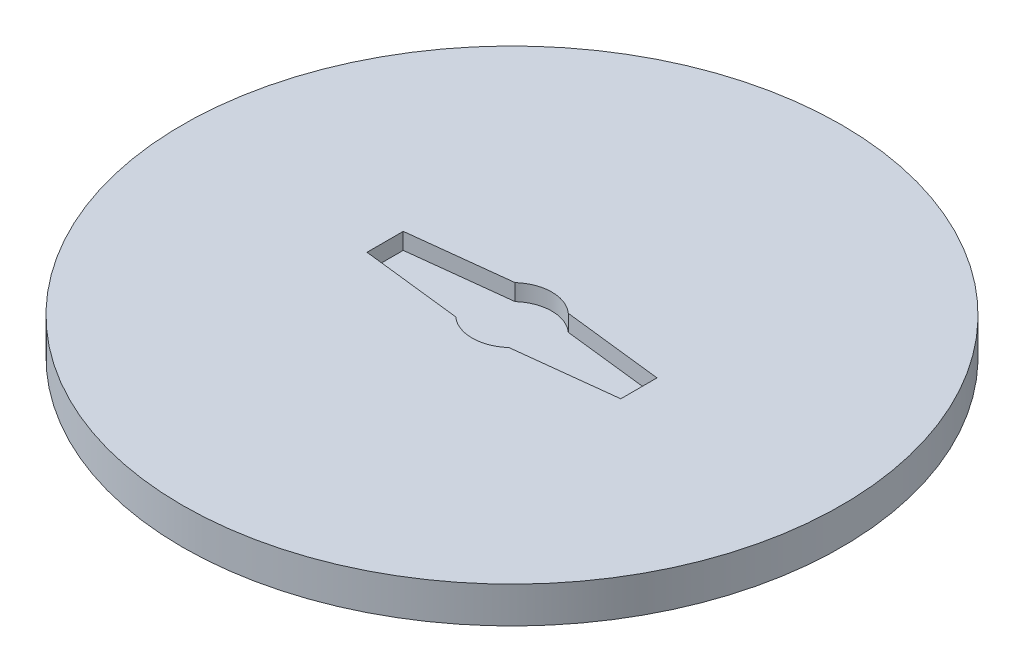
SolidWorks part; units mm, degrees
ref_plane "Front Plane" through (0, 0, 0) normal (0, 0, 1) x (1, 0, 0)
ref_plane "Top Plane" through (0, 0, 0) normal (0, 1, 0) x (1, 0, 0)
ref_plane "Right Plane" through (0, 0, 0) normal (1, 0, 0) x (0, 0, -1)
sketch "Sketch1" plane through (0, 0, 0) normal (0, 1, 0) x (1, 0, 0)
  circle A0 centre (0, 0) radius 50
extrude "Boss-Extrude1" add sketch "Sketch1" along normal blind 5.5
sketch "Sketch2" plane through (0, 5.5, 0) normal (0, 1, 0) x (1, 0, 0)
  line L0 (-4.0438, -4.5) -> (-19.25, -2.75)
  line L1 (19.25, -2.75) -> (4.0438, -4.5)
  line L3 (19.25, 2.75) -> (4.0438, 4.5)
  line L4 (-19.25, -2.75) -> (-19.25, 2.75)
  line L5 (-4.0438, 4.5) -> (-19.25, 2.75)
  line L6 (19.25, 0) -> (-19.25, 0) construction
  line L7 (19.25, 2.75) -> (19.25, -2.75)
  line L8 (4.0438, 4.5) -> (4.0438, -4.5) construction
  line L9 (-4.0438, 4.5) -> (-4.0438, -4.5) construction
  arc A0 (-4.0438, -4.5) -> (4.0438, -4.5) centre (0, 0) ccw
  arc A1 (4.0438, 4.5) -> (-4.0438, 4.5) centre (0, 0) ccw
  point P13 (0, 0)
  point P16 (19.25, 0)
  dimension "D1" = 38.5
  dimension "D3" = 6.05
  dimension "D2" = 9
  dimension "D4" = 9
extrude "Cut-Extrude1" cut sketch "Sketch2" against normal blind 2.5
